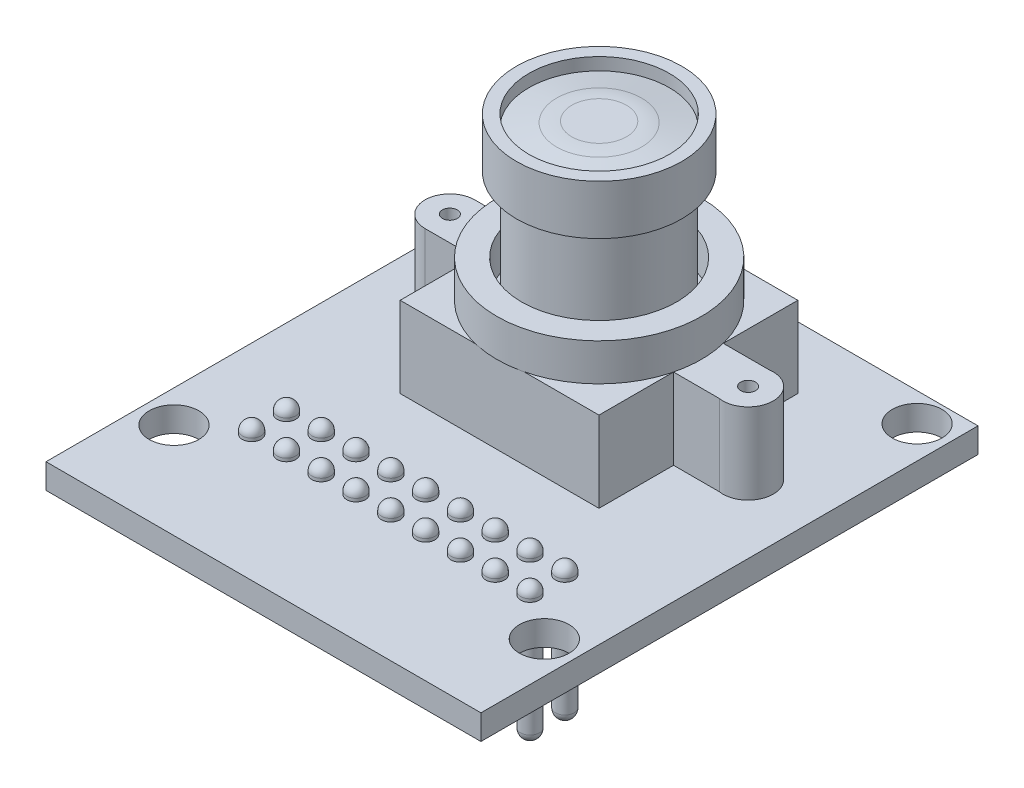
SolidWorks part; units mm, degrees
ref_plane "Front Plane" through (0, 0, 0) normal (0, 0, 1) x (1, 0, 0)
ref_plane "Top Plane" through (0, 0, 0) normal (0, 1, 0) x (1, 0, 0)
ref_plane "Right Plane" through (0, 0, 0) normal (1, 0, 0) x (0, 0, -1)
sketch "Board" plane through (0, 0, 0) normal (0, 1, 0) x (1, 0, 0)
  line L1 (-17.5, -20) -> (17.5, -20)
  line L2 (-17.5, -20) -> (-17.5, 20)
  line L3 (-17.5, 20) -> (17.5, 20)
  line L4 (17.5, -20) -> (17.5, 20)
  line L5 (-17.5, -20) -> (17.5, 20) construction
  line L6 (-17.5, 20) -> (17.5, -20) construction
  point P0 (0, 0)
  dimension "D1" = 35
  dimension "D2" = 40
extrude "BaseBoard" add sketch "Board" along normal blind 2
sketch "Sketch2" plane through (0, 2, 0) normal (0, 1, 0) x (1, 0, 0)
  line L0 (17.5, 20) -> (-17.5, 20) construction
  line L1 (17.5, -20) -> (17.5, 20) construction
  line L2 (14.9, 17.7) -> (14.9, -12.3) construction
  line L3 (0, 20) -> (0, 0) construction
  circle A0 centre (14.9, 17.7) radius 2
  circle A1 centre (14.9, -12.3) radius 2
  circle A2 centre (-14.9, -12.3) radius 2
  circle A3 centre (-14.9, 17.7) radius 2
  dimension "D1" = 4
  dimension "D2" = 2.3
  dimension "D3" = 2.6
  dimension "D4" = 30
extrude "Screw Holes" cut sketch "Sketch2" against normal blind 2
sketch "Sketch3" plane through (0, 2, 0) normal (0, 1, 0) x (1, 0, 0)
  line L0 (-12.5, 20) -> (-12.5, -20) construction
  line L1 (17.5, 20) -> (-17.5, 20) construction
  line L2 (-17.5, -20) -> (17.5, -20) construction
  line L3 (-17.5, 20) -> (-17.5, -20) construction
  line L4 (0, 0) -> (0, 8.4511) construction
  line L5 (12.5, 20) -> (12.5, -20) construction
  line L6 (-12.5, -11.5) -> (12.5, -11.5) construction
  line L7 (-12.5, -5.5) -> (12.5, -5.5) construction
  line L8 (-12.5, -5.5) -> (-12.5, -11.5) construction
  line L9 (-12.5, -11.5) -> (12.5, -11.5) construction
  line L10 (12.5, -11.5) -> (12.5, -5.5) construction
  circle A0 centre (-11.15, -7) radius 0.75
  circle A1 centre (-8.35, -7) radius 0.75
  circle A2 centre (-5.55, -7) radius 0.75
  circle A3 centre (-2.75, -7) radius 0.75
  circle A4 centre (0.05, -7) radius 0.75
  circle A5 centre (2.85, -7) radius 0.75
  circle A6 centre (5.65, -7) radius 0.75
  circle A7 centre (8.45, -7) radius 0.75
  circle A8 centre (11.25, -7) radius 0.75
  circle A9 centre (-8.35, -9.8) radius 0.75
  circle A10 centre (-5.55, -9.8) radius 0.75
  circle A11 centre (-2.75, -9.8) radius 0.75
  circle A12 centre (0.05, -9.8) radius 0.75
  circle A13 centre (2.85, -9.8) radius 0.75
  circle A14 centre (5.65, -9.8) radius 0.75
  circle A15 centre (8.45, -9.8) radius 0.75
  circle A16 centre (11.25, -9.8) radius 0.75
  circle A17 centre (-11.15, -9.8) radius 0.75
  dimension "D4" = 1.5
  dimension "D1" = 5
  dimension "D2" = 8.5
  dimension "D5" = 2.7
  dimension "D6" = 1.5
  dimension "D3" = 6
  dimension "D7" = 9
  dimension "D8" = 2
extrude "Pins" add sketch "Sketch3" along normal blind 1 and the other way blind 10
fillet "Fillet1" radius 0.75 36 edges at (11.25, -8, 7.75) (11.25, -8, 10.55) (8.45, -8, 7.75) (8.45, -8, 10.55) (5.65, -8, 7.75) (5.65, -8, 10.55) (2.85, -8, 7.75) (2.85, -8, 10.55) (0.05, -8, 7.75) (0.05, -8, 10.55) (-2.75, -8, 7.75) (-2.75, -8, 10.55) (-5.55, -8, 7.75) (-5.55, -8, 10.55) (-8.35, -8, 7.75) (-8.35, -8, 10.55) (-11.15, -8, 7.75) (-11.15, -8, 10.55) (0.05, 3, 10.55) (2.85, 3, 10.55) (5.65, 3, 10.55) (8.45, 3, 10.55) (11.25, 3, 10.55) (11.25, 3, 7.75) (8.45, 3, 7.75) (5.65, 3, 7.75) (2.85, 3, 7.75) (0.05, 3, 7.75) (-2.75, 3, 10.55) (-2.75, 3, 7.75) (-5.55, 3, 7.75) (-5.55, 3, 10.55) (-8.35, 3, 7.75) (-8.35, 3, 10.55) (-11.15, 3, 10.55) (-11.15, 3, 7.75)
sketch "Sketch4" plane through (0, 2, 0) normal (0, 1, 0) x (1, 0, 0)
  line L0 (0, 15) -> (0, -1) construction
  line L1 (-8, 5) -> (-8, -1)
  line L2 (8, 5) -> (8, -1)
  line L3 (-8, 15) -> (-8, 9)
  line L4 (8, 15) -> (8, 9)
  line L5 (-8, 15) -> (8, 15)
  line L7 (-8, -1) -> (8, -1)
  line L9 (-8, 20) -> (-8, -20) construction
  line L12 (8, 20) -> (8, -20) construction
  line L13 (0, 20) -> (0, -20) construction
  line L16 (-12, 5) -> (-8, 5)
  line L17 (8, 5) -> (12, 5)
  line L18 (-12, 9) -> (-8, 9)
  line L19 (8, 9) -> (12, 9)
  arc A0 (-12, 9) -> (-12, 5) centre (-12, 7) ccw
  arc A1 (11.6844, 5) -> (11.6844, 9) centre (12, 7) ccw
  circle A2 centre (-12, 7) radius 0.6
  circle A3 centre (12, 7) radius 0.6
  dimension "D5" = 1.2
  dimension "D1" = 8
  dimension "D2" = 8
extrude "Boss-Extrude3" add sketch "Sketch4" along normal blind 6.5 separate body
sketch "Sketch5" plane through (0, 8.5, 0) normal (0, 1, 0) x (1, 0, 0)
  line L0 (14.0247, 7) -> (-14, 7) construction
  line L1 (0, 15) -> (0, -1) construction
  line L2 (-8, 15) -> (8, 15) construction
  line L3 (-8, -1) -> (8, -1) construction
  arc A0 (11.6844, 5) -> (11.6844, 9) centre (12, 7) ccw construction
  arc A1 (-12, 9) -> (-12, 5) centre (-12, 7) ccw construction
  circle A2 centre (0.0124, 7) radius 8.2342
  circle A3 centre (0.0124, 7) radius 6.2342
  dimension "D1" = 2
extrude "Boss-Extrude4" add sketch "Sketch5" along normal blind 3 separate body
sketch "Sketch6" plane through (0, 11.5, 0) normal (0, 1, 0) x (1, 0, 0)
  circle A0 centre (0.0124, 7) radius 5.6049
  circle A1 centre (0.0124, 7) radius 4.8049
  dimension "D1" = 0.8
extrude "Boss-Extrude5" add sketch "Sketch6" along normal blind 6 and the other way blind 3 separate body
sketch "Sketch7" plane through (0, 17.5, 0) normal (0, 1, 0) x (1, 0, 0)
  circle A0 centre (0.0124, 7) radius 6.65
  circle A1 centre (0.0124, 7) radius 5.65
  dimension "D1" = 13.3
  dimension "D2" = 1
extrude "Boss-Extrude6" add sketch "Sketch7" along normal blind 4 separate body
ref_plane "Plane1" through (0, 20.5, 0) normal (0, 1, 0) x (1, 0, 0)
sketch "Sketch9" plane through (0, 20.5, 0) normal (0, 1, 0) x (1, 0, 0)
  circle A0 centre (0.0124, 7) radius 5.65
  circle A1 centre (0.0124, 7) radius 4.8049 construction
  dimension "D1" = 11.3
extrude "Glass" add sketch "Sketch9" along normal blind 0.5 draft 80 separate body
fillet "Fillet2" radius 7 1 edges at (0.0124, 21, -4.1856)
